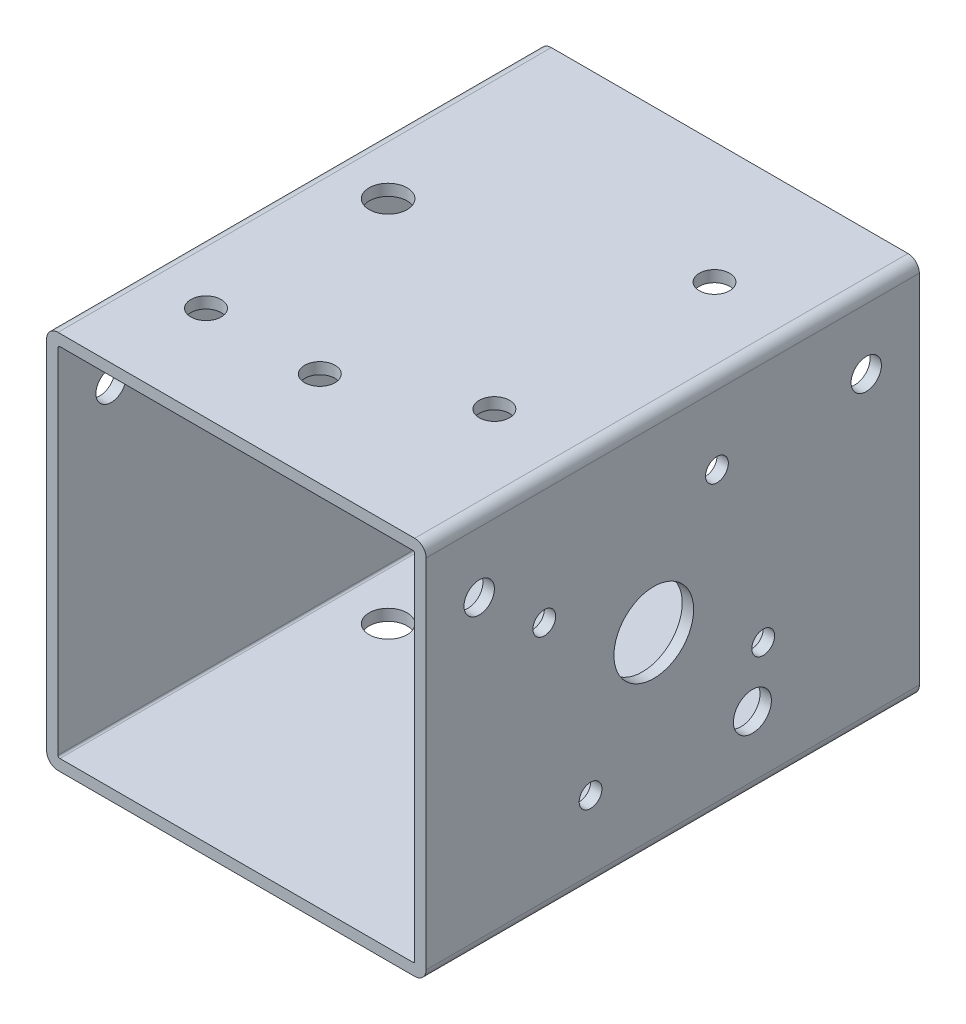
SolidWorks part; units mm, degrees
ref_plane "Front Plane" through (0, 0, 0) normal (0, 0, 1) x (1, 0, 0)
ref_plane "Top Plane" through (0, 0, 0) normal (0, 1, 0) x (1, 0, 0)
ref_plane "Right Plane" through (0, 0, 0) normal (1, 0, 0) x (0, 0, -1)
sketch "Sketch1" plane through (0, 0, 0) normal (0, 0, 1) x (1, 0, 0)
  line L1 (-50, 50) -> (50, 50)
  line L2 (-50, 50) -> (-50, -50)
  line L3 (-50, -50) -> (50, -50)
  line L4 (50, 50) -> (50, -50)
  line L5 (-50, 50) -> (50, -50) construction
  line L6 (-50, -50) -> (50, 50) construction
  point P0 (0, 0)
  dimension "D1" = 100
  dimension "D2" = 100
extrude "Extrude-Thin1" add sketch "Sketch1" along normal blind 130 thin
fillet "Fillet1" radius 0.5 4 edges at (-47, -47, 65) (-47, 47, 65) (47, 47, 65) (47, -47, 65)
fillet "Fillet2" radius 3 4 edges at (50, -50, 65) (-50, -50, 65) (50, 50, 65) (-50, 50, 65)
sketch "Holes - top" plane through (0, 0, 0) normal (0, 1, 0) x (1, 0, 0)
  line L0 (-3, 0) -> (-3, -130) construction
  line L1 (47, -130) -> (-47, -130) construction
  line L2 (-23, 0) -> (-23, -130) construction
  line L3 (47, 0) -> (-47, 0) construction
  line L4 (17, 0) -> (17, -130) construction
  circle A0 centre (-34, -56) radius 11 construction
  circle A1 centre (28, -90) radius 11 construction
  circle A2 centre (28, -32) radius 11 construction
  dimension "D4" = 22
  dimension "D1" = 40
  dimension "D2" = 40
  dimension "D3" = 32
  dimension "D5" = 56
  dimension "D6" = 3
hole_wizard "Ø8.0 (8) Diameter Hole2" positions "Sketch6" profile "Sketch5" hole size "Ø8.0" standard "ANSI Metric" end condition through all
sketch "Sketch6" plane through (0, 50, 0) normal (0, 1, 0) x (1, 0, 0)
  point P0 (28, -32)
  point P6 (28, -90)
sketch "Sketch5" plane through (28, 50, 32) normal (1, 0, 0) x (0, 0, 1)
  line L0 (0, 0) -> (0, 100)
  line L1 (0, 100) -> (4, 100)
  line L2 (4, 100) -> (4, 0)
  line L5 (4, 0) -> (0, 0)
  line L11 (0, -6.35) -> (0, 107.95) construction
  dimension "Thru Hole Dia." = 8
  dimension "Thru Hole Depth" = 100
sketch "Holes - side" plane through (0, 0, 0) normal (1, 0, 0) x (0, 0, -1)
  line L0 (0, 0) -> (-130, 0) construction
  line L1 (-130, -47) -> (-130, 47) construction
  line L2 (-130, 20) -> (0, 20) construction
  line L3 (0, -47) -> (0, 47) construction
  line L4 (-130, -20) -> (0, -20) construction
  circle A0 centre (-116, 31) radius 11 construction
  circle A1 centre (-14, 31) radius 11 construction
  circle A2 centre (-44, -31) radius 11 construction
  dimension "D1" = 40
  dimension "D2" = 22
  dimension "D3" = 14
  dimension "D4" = 14
  dimension "D5" = 44
hole_wizard "Ø8.0 (8) Diameter Hole3" positions "Sketch9" profile "Sketch8" hole size "Ø8.0" standard "ANSI Metric" end condition through all
sketch "Sketch9" plane through (50, 0, 0) normal (1, 0, 0) x (0, 0, -1)
  point P0 (-14, 31)
  point P3 (-116, 31)
sketch "Sketch8" plane through (50, 31, 14) normal (0, 1, 0) x (0, 0, -1)
  line L0 (0, 0) -> (0, 100)
  line L1 (0, 100) -> (4, 100)
  line L2 (4, 100) -> (4, 0)
  line L5 (4, 0) -> (0, 0)
  line L11 (0, -6.35) -> (0, 107.95) construction
  dimension "Thru Hole Dia." = 8
  dimension "Thru Hole Depth" = 100
hole_wizard "Ø10.0 (10) Diameter Hole1" positions "Sketch12" profile "Sketch11" hole size "Ø10.0" standard "ANSI Metric" end condition through all
sketch "Sketch12" plane through (0, 50, 0) normal (0, 1, 0) x (1, 0, 0)
  point P0 (-34, -56)
sketch "Sketch11" plane through (-34, 50, 56) normal (1, 0, 0) x (0, 0, 1)
  line L0 (0, 0) -> (0, 100)
  line L1 (0, 100) -> (5, 100)
  line L2 (5, 100) -> (5, 0)
  line L5 (5, 0) -> (0, 0)
  line L11 (0, -6.35) -> (0, 107.95) construction
  dimension "Thru Hole Dia." = 10
  dimension "Thru Hole Depth" = 100
hole_wizard "Ø10.0 (10) Diameter Hole2" positions "Sketch14" profile "Sketch13" hole size "Ø10.0" standard "ANSI Metric" end condition through all
sketch "Sketch14" plane through (50, 0, 0) normal (1, 0, 0) x (0, 0, -1)
  point P0 (-44, -31)
sketch "Sketch13" plane through (50, -31, 44) normal (0, 1, 0) x (0, 0, -1)
  line L0 (0, 0) -> (0, 100)
  line L1 (0, 100) -> (5, 100)
  line L2 (5, 100) -> (5, 0)
  line L5 (5, 0) -> (0, 0)
  line L11 (0, -6.35) -> (0, 107.95) construction
  dimension "Thru Hole Dia." = 10
  dimension "Thru Hole Depth" = 100
hole_wizard "Ø6.0 (6) Diameter Hole2" positions "Sketch18" profile "Sketch17" hole size "Ø6.0" standard "ANSI Metric"
sketch "Sketch18" plane through (-50, 0, 0) normal (-1, 0, 0) x (0, 0, 1)
  line L0 (56, 35) -> (56, -15) construction
  point P0 (56, -15)
  point P2 (56, 35)
  dimension "D1" = 56
  dimension "D2" = 35
  dimension "D3" = 15
sketch "Sketch17" plane through (-50, -15, 56) normal (0, 1, 0) x (0, 0, 1)
  line L0 (0, 0) -> (0, 3)
  line L1 (0, 3) -> (3, 3)
  line L2 (3, 3) -> (3, 0)
  line L5 (3, 0) -> (0, 0)
  line L11 (0, -6.35) -> (0, 107.95) construction
  dimension "Thru Hole Dia." = 6
  dimension "Thru Hole Depth" = 3
hole_wizard "Ø6.0 (6) Diameter Hole3" positions "Sketch21" profile "Sketch20" hole size "Ø6.0" standard "ANSI Metric"
sketch "Sketch21" plane through (0, -50, 0) normal (0, -1, 0) x (-1, 0, 0)
  line L0 (20, -44) -> (-35, -44) construction
  point P0 (20, -44)
  point P2 (-35, -44)
  dimension "D1" = 44
  dimension "D2" = 35
  dimension "D3" = 20
sketch "Sketch20" plane through (-20, -50, 44) normal (1, 0, 0) x (0, 0, -1)
  line L0 (0, 0) -> (0, 3)
  line L1 (0, 3) -> (3, 3)
  line L2 (3, 3) -> (3, 0)
  line L5 (3, 0) -> (0, 0)
  line L11 (0, -6.35) -> (0, 107.95) construction
  dimension "Thru Hole Dia." = 6
  dimension "Thru Hole Depth" = 3
sketch "Holes - Nema 23 motor" plane through (0, 0, 0) normal (1, 0, 0) x (0, 0, -1)
  line L0 (-98.8427, 16.6524) -> (-53.3476, 28.8427) construction
  line L1 (-98.8427, 16.6524) -> (-86.6524, -28.8427) construction
  line L2 (-53.3476, 28.8427) -> (-41.1573, -16.6524) construction
  line L3 (-86.6524, -28.8427) -> (-41.1573, -16.6524) construction
  line L4 (-98.8427, 16.6524) -> (-41.1573, -16.6524) construction
  line L5 (-53.3476, 28.8427) -> (-86.6524, -28.8427) construction
  line L6 (0, 0) -> (-130, 0) construction
  point P1 (-70, 0)
  dimension "D1" = 70
  dimension "D2" = 47.1
  dimension "D3" = 47.1
  dimension "D4" = 15
hole_wizard "Ø21.0 (21) Diameter Hole1" positions "Sketch24" profile "Sketch23" hole size "Ø21.0" standard "ANSI Metric"
sketch "Sketch24" plane through (50, 0, 0) normal (1, 0, 0) x (0, 0, -1)
  point P0 (-70, 0)
sketch "Sketch23" plane through (50, 0, 70) normal (0, 1, 0) x (0, 0, -1)
  line L0 (0, 0) -> (0, 3)
  line L1 (0, 3) -> (10.5, 3)
  line L2 (10.5, 3) -> (10.5, 0)
  line L5 (10.5, 0) -> (0, 0)
  line L11 (0, -6.35) -> (0, 107.95) construction
  dimension "Thru Hole Dia." = 21
  dimension "Thru Hole Depth" = 3
hole_wizard "Ø6.0 (6) Diameter Hole1" positions "Sketch26" profile "Sketch25" hole size "Ø6.0" standard "ANSI Metric"
sketch "Sketch26" plane through (50, 0, 0) normal (1, 0, 0) x (0, 0, -1)
  point P0 (-41.1573, -16.6524)
  point P3 (-53.3476, 28.8427)
  point P6 (-98.8427, 16.6524)
  point P9 (-86.6524, -28.8427)
sketch "Sketch25" plane through (50, -16.6524, 41.1573) normal (0, 1, 0) x (0, 0, -1)
  line L0 (0, 0) -> (0, 3)
  line L1 (0, 3) -> (3, 3)
  line L2 (3, 3) -> (3, 0)
  line L5 (3, 0) -> (0, 0)
  line L11 (0, -6.35) -> (0, 107.95) construction
  dimension "Thru Hole Dia." = 6
  dimension "Thru Hole Depth" = 3
hole_wizard "Ø8.0 (8) Diameter Hole4" positions "Sketch29" profile "Sketch28" hole size "Ø8.0" standard "ANSI Metric"
sketch "Sketch29" plane through (0, 50, 0) normal (0, 1, 0) x (1, 0, 0)
  line L0 (-3, 0) -> (-3, -130) construction
  point P0 (-3, -105)
  dimension "D1" = 15
sketch "Sketch28" plane through (-3, 50, 105) normal (1, 0, 0) x (0, 0, 1)
  line L0 (0, 0) -> (0, 3)
  line L1 (0, 3) -> (4, 3)
  line L2 (4, 3) -> (4, 0)
  line L5 (4, 0) -> (0, 0)
  line L11 (0, -6.35) -> (0, 107.95) construction
  dimension "Thru Hole Dia." = 8
  dimension "Thru Hole Depth" = 3
sketch "Sketch32" plane through (50, 0, 0) normal (1, 0, 0) x (0, 0, -1)
  line L1 (0, -47) -> (0, 47) construction
  line L2 (-65, 69.5535) -> (-65, -72.7704) construction
  line L3 (-130, -47) -> (-130, 47) construction
  line L4 (-130, 50) -> (0, 50) construction
  circle A0 centre (-5, 13) radius 2
  circle A1 centre (-5, 4) radius 2
  circle A2 centre (-125, 4) radius 2
  circle A3 centre (-125, 13) radius 2
  dimension "D1" = 46
  dimension "D2" = 9
  dimension "D3" = 4
  dimension "D5" = 5
  dimension "D4" = 0
  dimension "D6" = 65
sketch "Sketch33" plane through (0, 50, 0) normal (0, 1, 0) x (1, 0, 0)
  line L0 (47, -130) -> (-47, -130) construction
  circle A0 centre (-33, -105) radius 4
  circle A2 centre (-3, -105) radius 4 construction
  dimension "D3" = 8
  dimension "D1" = 25
  dimension "D2" = 30
extrude "Cut-Extrude1" cut sketch "Sketch33" against normal blind 10
equation "\"L\"= 130"
equation "\"D1@Extrude-Thin1\"=\"L\""
equation "\"d-bearing\"= 22'diameter of bearing"
equation "\"D4@Holes - top\"=\"d-bearing\""
equation "\"D2@Holes - side\"=\"d-bearing\""
